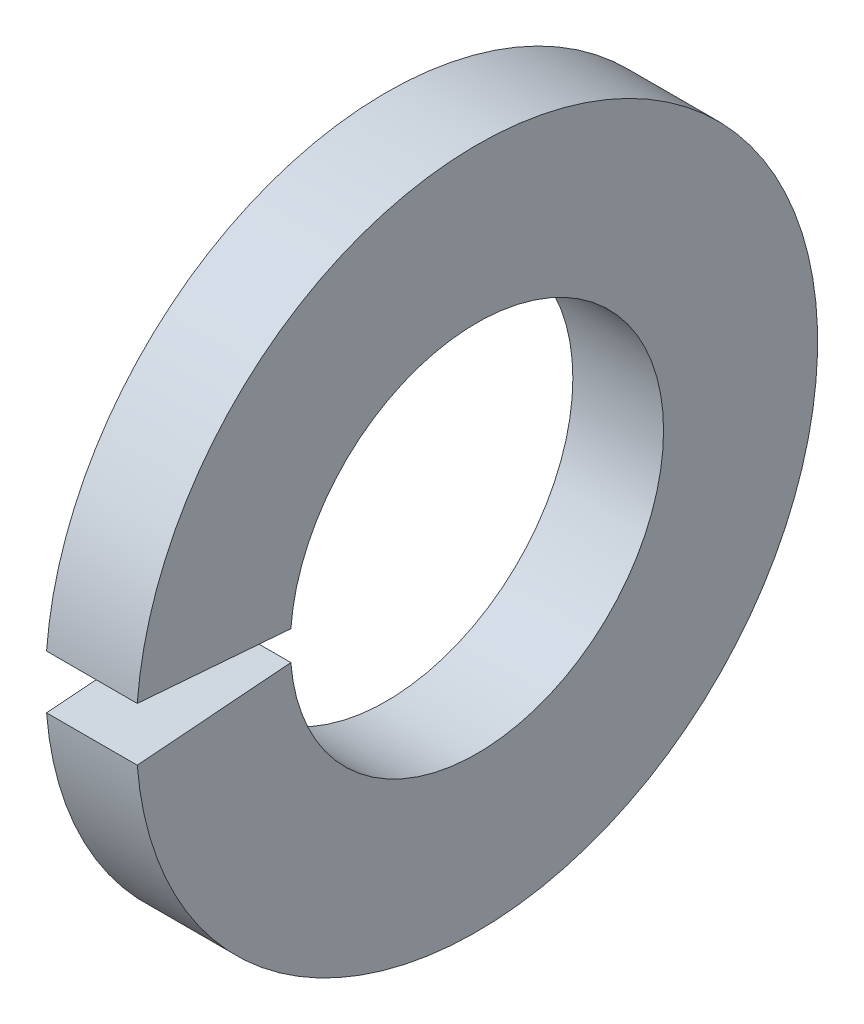
SolidWorks part; units mm, degrees
ref_plane "Plane1" through (0, 0, 0) normal (0, 0, 1) x (1, 0, 0)
ref_plane "Plane2" through (0, 0, 0) normal (0, 1, 0) x (1, 0, 0)
ref_plane "Plane3" through (0, 0, 0) normal (1, 0, 0) x (0, 0, -1)
sketch "Sketch1" plane through (0, 0, 0) normal (0, 0, 1) x (1, 0, 0)
  line L0 (-34.925, 0) -> (9.525, 0) construction
  line L1 (0, 4.0767) -> (0, 7.4422)
  line L2 (0, 7.4422) -> (-1.9812, 7.4422)
  line L3 (-1.9812, 7.4422) -> (-1.9812, 4.0767)
  line L4 (-1.9812, 4.0767) -> (0, 4.0767)
  dimension "Thickness" = 1.9812
  dimension "Inside_dia" = 8.1534
  dimension "Outside_dia" = 14.8844
revolve "Base-Revolve" add sketch "Sketch1" angle 360 about L0
sketch "Sketch2" plane through (0, 0, 0) normal (-1, 0, 0) x (0, -1, 0)
  line L0 (0, 0) -> (0.5956, 7.5676)
  line L1 (0, -3.175) -> (0, 12.7) construction
  line L2 (0, 0) -> (-0.5956, 7.5676)
  arc A0 (0.5956, 7.5676) -> (-0.5956, 7.5676) centre (0, 0) ccw
  dimension "Gap_ang" = 9
  dimension "D1" = 7.591
extrude "Gap" cut sketch "Sketch2" along normal through all
equation "\"D1@Sketch2\" = \"Outside_dia@Sketch1\" * 0.51"
